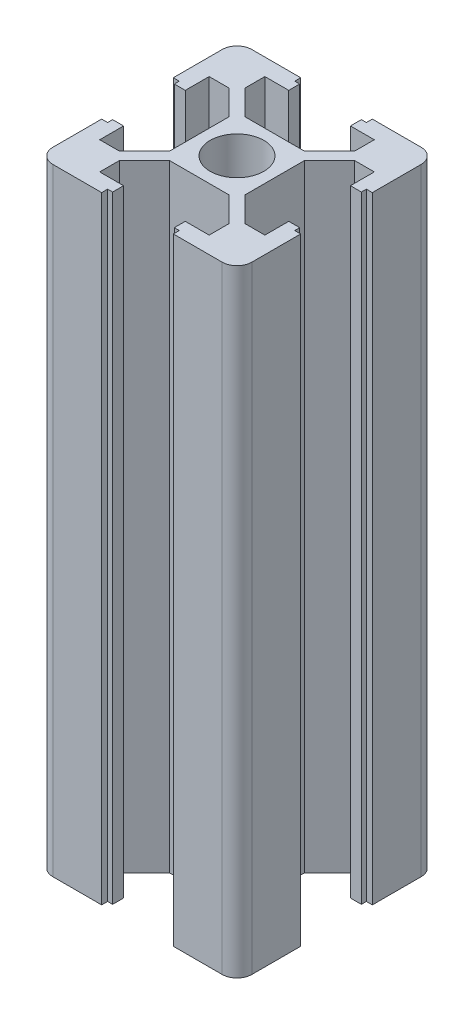
SolidWorks part; units mm, degrees
material "氧化铝"
ref_plane "前视基准面" through (0, 0, 0) normal (0, 0, 1) x (1, 0, 0)
ref_plane "上视基准面" through (0, 0, 0) normal (0, 1, 0) x (1, 0, 0)
ref_plane "右视基准面" through (0, 0, 0) normal (1, 0, 0) x (0, 0, -1)
sketch "草图1" plane through (0, 0, 0) normal (0, 1, 0) x (1, 0, 0)
  line L1 (-10, 10) -> (10, 10)
  line L2 (-10, 10) -> (-10, -10)
  line L3 (-10, -10) -> (10, -10)
  line L4 (10, 10) -> (10, -10)
  line L5 (-10, 10) -> (10, -10) construction
  line L6 (-10, -10) -> (10, 10) construction
  point P0 (0, 0)
  dimension "D1" = 20
  dimension "D2" = 20
extrude "凸台-拉伸1" add sketch "草图1" along normal mid plane 62
sketch "草图4" plane through (0, 31, 0) normal (0, 1, 0) x (1, 0, 0)
  circle A0 centre (0, 0) radius 2.7
  dimension "D1" = 5.4
extrude "切除-拉伸3" cut sketch "草图4" against normal blind 9999
sketch "草图2" plane through (0, 31, 0) normal (0, 1, 0) x (1, 0, 0)
  line L0 (10, 10) -> (-10, 10) construction
  line L1 (-3.6, 10.6) -> (3.6, 10.6)
  line L2 (-3.6, 10.6) -> (-3.6, 9.4)
  line L3 (-3.6, 9.4) -> (3.6, 9.4)
  line L4 (3.6, 10.6) -> (3.6, 9.4)
  line L5 (-3.6, 10.6) -> (3.6, 9.4) construction
  line L6 (-3.6, 9.4) -> (3.6, 10.6) construction
  line L8 (-3.1, 11.7) -> (3.1, 11.7)
  line L9 (-3.1, 11.7) -> (-3.1, 8.3)
  line L10 (-3.1, 8.3) -> (3.1, 8.3)
  line L11 (3.1, 11.7) -> (3.1, 8.3)
  line L12 (-3.1, 11.7) -> (3.1, 8.3) construction
  line L13 (-3.1, 8.3) -> (3.1, 11.7) construction
  point P0 (0, 10)
  point P7 (0, 10)
  dimension "D1" = 1.2
  dimension "D2" = 3.4
  dimension "D3" = 7.2
  dimension "D4" = 6.2
extrude "切除-拉伸1" cut sketch "草图2" against normal blind 9999 contours L2 L3 L4 L1 | L10 L11 L8 L9
sketch "草图3" plane through (0, 31, 0) normal (0, 1, 0) x (1, 0, 0)
  line L5 (5.5, 8.3) -> (-5.5, 8.3)
  line L6 (-3.1, 8.3) -> (3.1, 8.3) construction
  line L7 (-5.5, 8.3) -> (-5.5, 6.3)
  line L8 (-3, 3.8) -> (3, 3.8)
  line L9 (0, 3.8) -> (0, 8.3) construction
  line L12 (-5.5, 6.3) -> (-3, 3.8)
  line L13 (5.5, 6.3) -> (3, 3.8)
  line L14 (5.5, 8.3) -> (5.5, 6.3)
  dimension "D1" = 5.5
  dimension "D2" = 4.5
  dimension "D3" = 2
  dimension "D4" = 3
extrude "切除-拉伸2" cut sketch "草图3" against normal blind 9999
pattern_circular "阵列(圆周)5" count 4 over 360 about axis through (0, 0, 0) along (0, 1, 0) of "切除-拉伸1", "切除-拉伸2"
fillet "圆角1" radius 1.5 4 edges at (-10, 0, 10) (10, 0, 10) (-10, 0, -10) (10, 0, -10)
